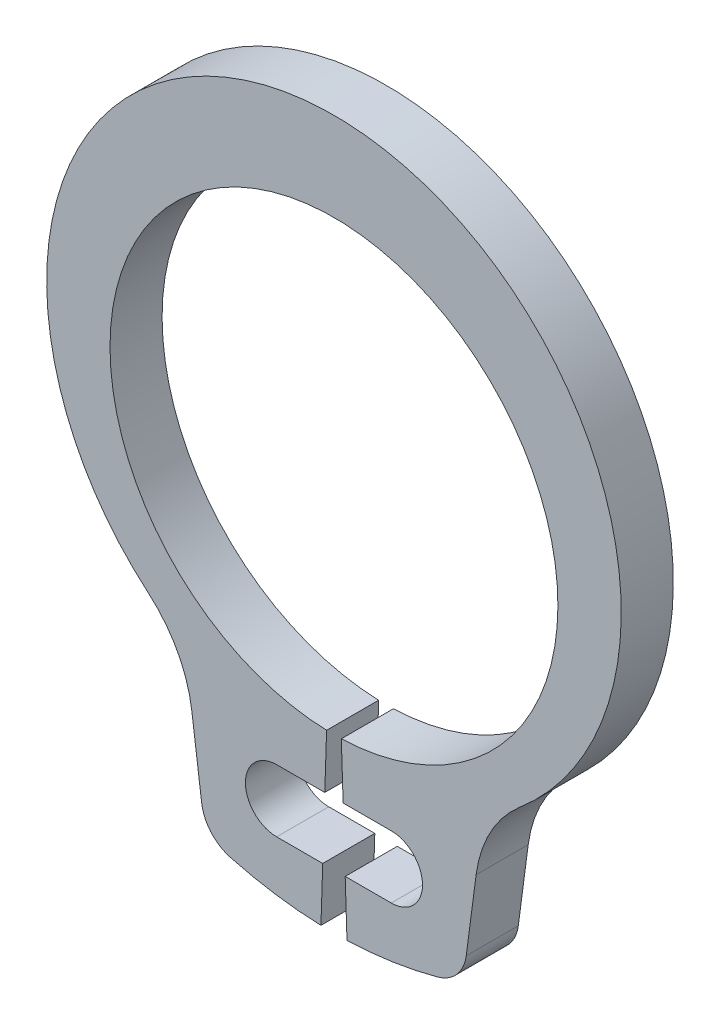
SolidWorks part; units mm, degrees
ref_plane "Plane1" through (0, 0, 0) normal (0, 0, 1) x (1, 0, 0)
ref_plane "Plane2" through (0, 0, 0) normal (0, 1, 0) x (1, 0, 0)
ref_plane "Plane3" through (0, 0, 0) normal (1, 0, 0) x (0, 0, -1)
other "Configuration Table"
sketch "Clipboard" plane through (0, 0, 0) normal (0, 0, 1) x (1, 0, 0)
  line L0 (0, 0) -> (1.7, 0)
  line L1 (0, 0) -> (0, 0.85)
  line L2 (0, 0) -> (0, -3.3)
  circle A0 centre (0, 0) radius 0.6
  circle A1 centre (0, 0) radius 4.5
  dimension "HoleDia" = 1.2
  dimension "ShaftDia" = 9
  dimension "LargeSection" = 1.7
  dimension "SmallSection" = 0.85
  dimension "LugSection" = 3.3
sketch "BodySke" plane through (0, 0, 0) normal (0, 0, 1) x (1, 0, 0)
  line L0 (-1.5431, 0) -> (1.5431, 0) construction
  line L1 (0, 0) -> (0, 6) construction
  line L2 (0.1414, -4.2977) -> (0.25, -7.5959)
  line L3 (-0.1414, -4.2977) -> (-0.25, -7.5959)
  line L4 (0, 0) -> (5.1556, -5.5839) construction
  line L5 (0, 0) -> (-5.1556, -5.5839) construction
  line L7 (2.7296, -5.2645) -> (2.5395, -6.7083)
  line L8 (-2.7296, -5.2645) -> (-2.5395, -6.7083)
  circle A0 centre (0, 0) radius 4.3 construction
  arc A1 (0.1414, -4.2977) -> (-0.1414, -4.2977) centre (0, 0) ccw
  arc A2 (3.4936, -3.7838) -> (-3.4936, -3.7838) centre (0, 0.4843) ccw construction
  arc A3 (0.25, -7.5959) -> (1.9925, -7.3342) centre (0, 0) ccw
  arc A4 (3.5712, -3.7191) -> (2.7296, -5.2645) centre (5.1556, -5.5839) ccw
  arc A5 (-2.7296, -5.2645) -> (-3.5712, -3.7191) centre (-5.1556, -5.5839) ccw
  arc A6 (-1.9925, -7.3342) -> (-0.25, -7.5959) centre (0, 0) ccw
  arc A7 (3.5712, -3.7191) -> (-3.5712, -3.7191) centre (0, 0.4843) ccw
  arc A8 (-2.7106, -5.4088) -> (2.7106, -5.4088) centre (0, 0) ccw construction
  circle A9 centre (1.1, -5.9492) radius 0.6
  circle A10 centre (-1.1, -5.9492) radius 0.6
  arc A11 (2.5395, -6.7083) -> (1.9925, -7.3342) centre (1.7959, -6.6104) cw
  arc A12 (-2.5395, -6.7083) -> (-1.9925, -7.3342) centre (-1.7959, -6.6104) ccw
  point P28 (2.4767, -7.1851)
  point P31 (-2.4767, -7.1851)
  dimension "HoleDia" = 1.2
  dimension "GrooveDia" = 8.6
  dimension "LugRad" = 7.6
  dimension "HoleOffsetRad" = 6.05
  dimension "D3" = 0.75
  dimension "LargeRad" = 6
  dimension "SmallRad" = 5.15
  dimension "SmallAngle" = 85.433
  dimension "D2" = 15
  dimension "HoleSpacing" = 2.2
  dimension "Gap" = 0.5
extrude "Body" add sketch "BodySke" against normal blind 1
sketch "NotSke" plane through (0, 0, 0) normal (0, 0, 1) x (1, 0, 0)
  line L0 (1.1, -5.3492) -> (1.1, -6.5492)
  line L1 (1.1, -6.5492) -> (-1.1, -6.5492)
  line L2 (-1.1, -6.5492) -> (-1.1, -5.3492)
  line L3 (-1.1, -5.3492) -> (1.1, -5.3492)
  circle A0 centre (1.1, -5.9492) radius 0.6 construction
  circle A1 centre (-1.1, -5.9492) radius 0.6 construction
extrude "Notch" cut sketch "NotSke" against normal through all
sketch "UnlSke" plane through (0, 0, 0) normal (0, 0, 1) x (1, 0, 0)
  line L0 (-2.1162, -7.2994) -> (-1.1973, -4.1299)
  line L1 (2.1162, -7.2994) -> (1.1973, -4.1299)
  arc A0 (1.1973, -4.1299) -> (-1.1973, -4.1299) centre (0, 0) ccw
  arc A1 (2.1162, -7.2994) -> (-2.1162, -7.2994) centre (0, 0) ccw
  arc A2 (0.25, -7.5959) -> (1.9925, -7.3342) centre (0, 0) ccw construction
  arc A3 (0.1414, -4.2977) -> (-0.1414, -4.2977) centre (0, 0) ccw construction
  circle A4 centre (-1.1, -5.9492) radius 0.6 construction
  circle A5 centre (1.1, -5.9492) radius 0.6 construction
extrude "Unlug" [suppressed] add sketch "UnlSke" against normal through all
equation "' \"ShaftDia@Clipboard\" = 3"
equation "' \"Thickness@Body\" = 0.4"
equation "' \"GrooveDia@BodySke\" = 2.8"
equation "' \"LugSection@Clipboard\" = 1.9"
equation "' \"LargeSection@Clipboard\" = 0.8"
equation "' \"HoleDia@Clipboard\" = 1.0"
equation "' \"ShaftDia@Clipboard\" = 10"
equation "' \"Thickness@Body\" = 1.0"
equation "' \"GrooveDia@BodySke\" = 9.6"
equation "' \"LugSection@Clipboard\" = 3.3"
equation "' \"LargeSection@Clipboard\" = 1.8"
equation "' \"HoleDia@Clipboard\" = 1.5"
equation "\"SmallSection@Clipboard\" = \"LargeSection@Clipboard\" * 0.5"
equation "\"Gap@BodySke\" =  \"Thickness@Body\" / 2"
equation "\"LargeRad@BodySke\" =  \"GrooveDia@BodySke\" / 2 +  \"LargeSection@Clipboard\""
equation "\"SmallRad@BodySke\" =  \"GrooveDia@BodySke\" / 2 +  \"SmallSection@Clipboard\""
equation "\"LugRad@BodySke\" = \"GrooveDia@BodySke\" / 2 + \"LugSection@Clipboard\""
equation "\"HoleOffsetRad@BodySke\" = (  \"ShaftDia@Clipboard\" / 2 + \"LugRad@BodySke\" ) / 2"
equation "\"HoleSpacing@BodySke\" = \"Gap@BodySke\"  * 2 +  \"HoleDia@Clipboard\""
equation "\"HoleDia@BodySke\" =  \"HoleDia@Clipboard\""
equation "\"SmallAngle@BodySke\" = atn(\"HoleSpacing@BodySke\" / 2 / sqr(\"HoleOffsetRad@BodySke\"  * \"HoleOffsetRad@BodySke\" - (\"HoleSpacing@BodySke\" / 2) * (\"HoleSpacing@BodySke\" / 2) ))  * 7 *  (\"LargeRad@BodySke\" / \"SmallRad@BodySke\")* ( 180 / 3.141593)"
